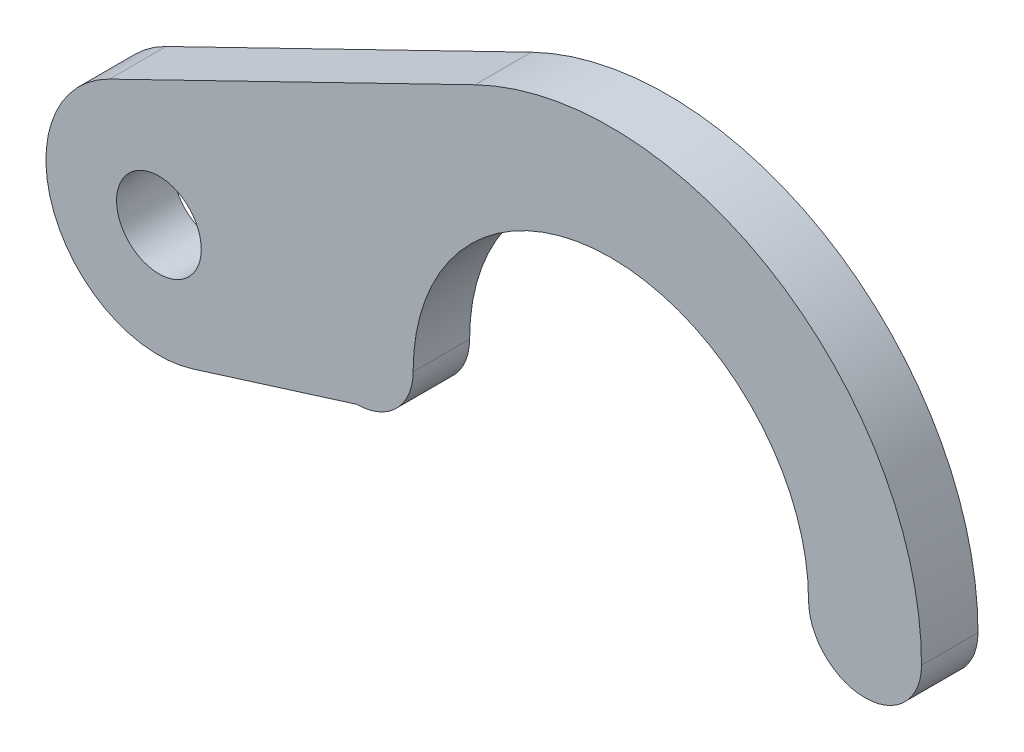
SolidWorks part; units mm, degrees
material "Acrylic (Medium-high impact)"
ref_plane "Front" through (0, 0, 0) normal (0, 0, 1) x (1, 0, 0)
ref_plane "Top" through (0, 0, 0) normal (0, 1, 0) x (1, 0, 0)
ref_plane "Right" through (0, 0, 0) normal (1, 0, 0) x (0, 0, -1)
sketch "Sketch1" plane through (0, 0, 0) normal (0, 0, 1) x (1, 0, 0)
  circle A0 centre (0, 0) radius 25.4
  dimension "D1" = 50.8
sketch "Sketch2" plane through (0, 0, 0) normal (0, 0, 1) x (1, 0, 0)
  line L0 (0, 0) -> (-93.9046, 0) construction
  line L1 (-56.3562, 11.4201) -> (-15.2797, 31.4052)
  line L2 (-47.0057, -12.12) -> (-28.575, -6.35)
  line L3 (0, 0) -> (100.627, 0) construction
  circle A0 centre (-50.8, 0) radius 4.7625
  arc A1 (-56.3562, 11.4201) -> (-47.0057, -12.12) centre (-50.8, 0) ccw
  arc A2 (22.225, 0) -> (-22.225, 0) centre (0, 0) ccw
  arc A3 (34.925, 0) -> (-15.2797, 31.4052) centre (0, 0) ccw
  arc A7 (22.225, 0) -> (34.925, 0) centre (28.575, 0) ccw
  arc A8 (-28.575, -6.35) -> (-22.225, 0) centre (-28.575, 0) ccw
  dimension "D1" = 9.525
  dimension "D2" = 25.4
  dimension "D3" = 44.45
  dimension "D4" = 69.85
  dimension "D5" = 50.8
extrude "Boss-Extrude1" add sketch "Sketch2" along normal blind 6.35
